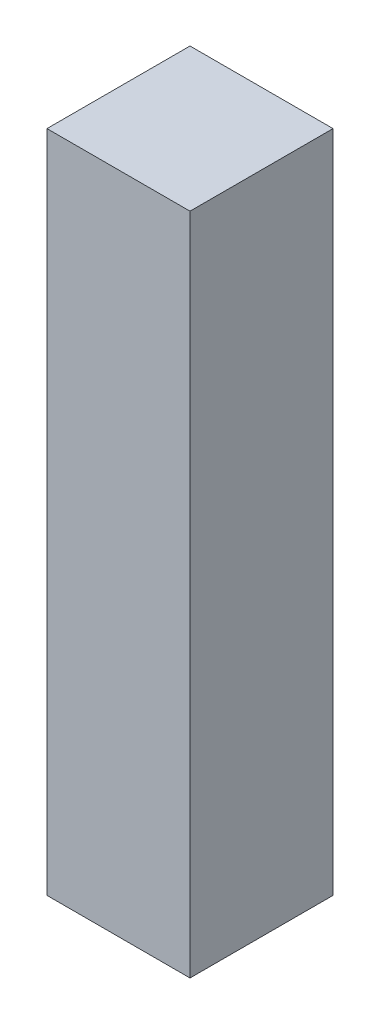
SolidWorks part; units mm, degrees
material "Balsa"
ref_plane "Alzado" through (0, 0, 0) normal (0, 0, 1) x (1, 0, 0)
ref_plane "Planta" through (0, 0, 0) normal (0, 1, 0) x (1, 0, 0)
ref_plane "Vista lateral" through (0, 0, 0) normal (1, 0, 0) x (0, 0, -1)
sketch "Croquis1" plane through (0, 0, 0) normal (0, 1, 0) x (1, 0, 0)
  line L1 (-3.5, -3.5) -> (3.5, -3.5)
  line L2 (-3.5, -3.5) -> (-3.5, 3.5)
  line L3 (-3.5, 3.5) -> (3.5, 3.5)
  line L4 (3.5, -3.5) -> (3.5, 3.5)
  line L5 (-3.5, -3.5) -> (3.5, 3.5) construction
  line L6 (-3.5, 3.5) -> (3.5, -3.5) construction
  point P0 (0, 0)
  dimension "D1" = 7
  dimension "D2" = 7
extrude "Saliente-Extruir1" add sketch "Croquis1" along normal mid plane 32.5
